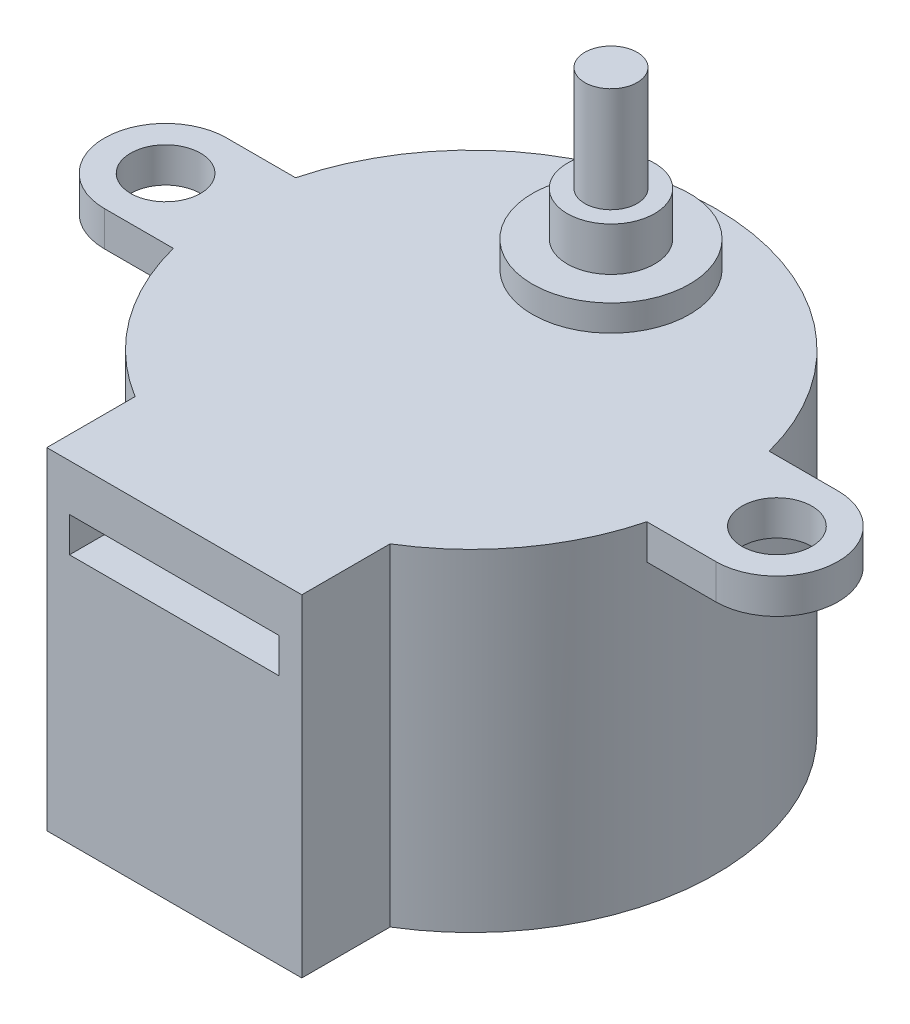
SolidWorks part; units mm, degrees
ref_plane "Front Plane" through (0, 0, 0) normal (0, 0, 1) x (1, 0, 0)
ref_plane "Top Plane" through (0, 0, 0) normal (0, 1, 0) x (1, 0, 0)
ref_plane "Right Plane" through (0, 0, 0) normal (1, 0, 0) x (0, 0, -1)
sketch "Sketch1" plane through (0, 0, 0) normal (0, 1, 0) x (1, 0, 0)
  line L0 (-7.3, -17) -> (-7.3, -11.9461)
  line L3 (0, -17) -> (7.3, -17)
  line L7 (0, -17) -> (-7.3, -17)
  line L9 (7.3, -17) -> (7.3, -11.9461)
  circle A0 centre (0, 0) radius 14
  dimension "D1" = 28
  dimension "D2" = 17
extrude "Boss-Extrude1" add sketch "Sketch1" along normal blind 19 contours A0 | A0 L0 L7 L3 L9
sketch "Sketch4" plane through (0, 19, 0) normal (0, 1, 0) x (1, 0, 0)
  line L2 (-17.5, -3.5) -> (-13.5554, -3.5)
  line L3 (-17.5, 3.5) -> (-13.5554, 3.5)
  line L4 (17.5, -3.5) -> (13.5554, -3.5)
  line L5 (17.5, 3.5) -> (13.5554, 3.5)
  circle A1 centre (-17.5, 0) radius 2
  arc A2 (7.3, -11.9461) -> (-7.3, -11.9461) centre (0, 0) ccw construction
  arc A3 (-17.5, 3.5) -> (-17.5, -3.5) centre (-17.5, 0) ccw
  circle A4 centre (17.5, 0) radius 2
  arc A5 (17.5, -3.5) -> (17.5, 3.5) centre (17.5, 0) ccw
  arc M6 (7.3, -11.9461) -> (-7.3, -11.9461) centre (0, 0) ccw
extrude "Boss-Extrude2" add sketch "Sketch4" against normal blind 2 contours L3 A3 L2 A1 M6 | L4 A5 L5 A4 M6
sketch "Sketch5" plane through (0, 19, 0) normal (0, 1, 0) x (1, 0, 0)
  circle A0 centre (0, 8) radius 4.5
  dimension "D1" = 9
  dimension "D2" = 8
extrude "Boss-Extrude3" add sketch "Sketch5" along normal blind 1.5
sketch "Sketch6" plane through (0, 20.5, 0) normal (0, 1, 0) x (1, 0, 0)
  circle A0 centre (0, 8) radius 2.5
  dimension "D1" = 5
extrude "Boss-Extrude4" add sketch "Sketch6" along normal blind 2.5
sketch "Sketch7" plane through (0, 23, 0) normal (0, 1, 0) x (1, 0, 0)
  circle A1 centre (0, 8) radius 1.5
  dimension "D1" = 3
extrude "Boss-Extrude5" add sketch "Sketch7" along normal blind 6 contours A1
sketch "Sketch8" plane through (0, 0, 17) normal (0, 0, 1) x (1, 0, 0)
  line L0 (-7.3, 19) -> (-7.3, 0) construction
  line L1 (-6, 16.3325) -> (6, 16.3325)
  line L2 (-6, 16.3325) -> (-6, 14.3325)
  line L3 (-6, 14.3325) -> (6, 14.3325)
  line L4 (6, 16.3325) -> (6, 14.3325)
  point P4 (-6, 15.3325)
  dimension "D1" = 12
  dimension "D2" = 2
  dimension "D3" = 1.3
extrude "Cut-Extrude1" cut sketch "Sketch8" against normal blind 4
